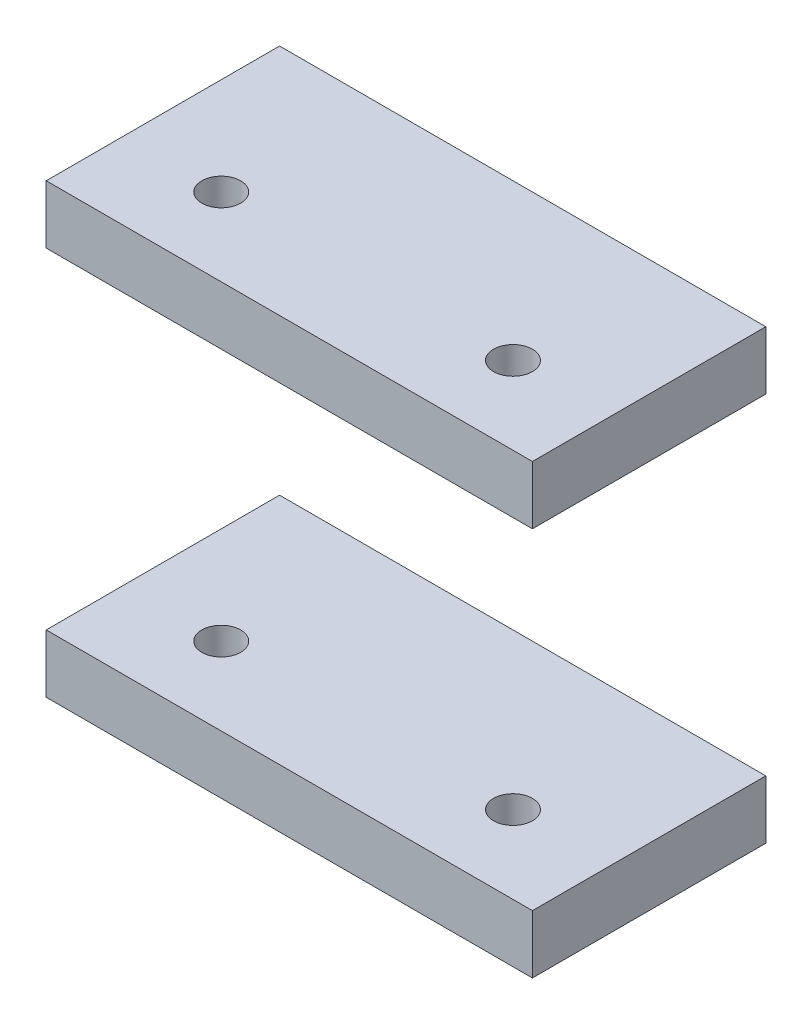
SolidWorks part; units mm, degrees
ref_plane "Front" through (0, 0, 0) normal (0, 0, 1) x (1, 0, 0)
ref_plane "Top" through (0, 0, 0) normal (0, 1, 0) x (1, 0, 0)
ref_plane "Right" through (0, 0, 0) normal (1, 0, 0) x (0, 0, -1)
sketch "草图1" plane through (0, 0, 0) normal (0, 0, 1) x (1, 0, 0)
  line L0 (25, -23) -> (-25, -23) construction
  line L1 (25, -23) -> (-25, -23)
  line L2 (25, 23) -> (-25, 23) construction
  line L3 (25, 23) -> (-25, 23)
  line L4 (25, -23) -> (25, 23) construction
  line L5 (-25, -23) -> (-25, 23) construction
  line L6 (25, -23) -> (25, -17)
  line L7 (-25, -23) -> (-25, -17)
  line L8 (-25, -17) -> (25, -17)
  line L9 (-25, 17) -> (25, 17)
  line L10 (-25, 17) -> (-25, 23)
  line L11 (25, 17) -> (25, 23)
  dimension "D1" = 6
  dimension "D2" = 6
extrude "凸台-拉伸1" add sketch "草图1" along normal blind 24 contours L8 L6 L1 L7 | L9 L11 L3 L10
sketch "草图2" plane through (0, -23, 0) normal (0, -1, 0) x (1, 0, 0)
  line L0 (25, 24) -> (-25, 24) construction
  line L1 (-25, 24) -> (-25, 0) construction
  circle A0 centre (-15, 16) radius 2
  circle A1 centre (15, 16) radius 2
  point P10 (0, 0)
  dimension "D1" = 4
  dimension "D2" = 30
  dimension "D3" = 8
  dimension "D4" = 10
extrude "切除-拉伸1" cut sketch "草图2" against normal through all
